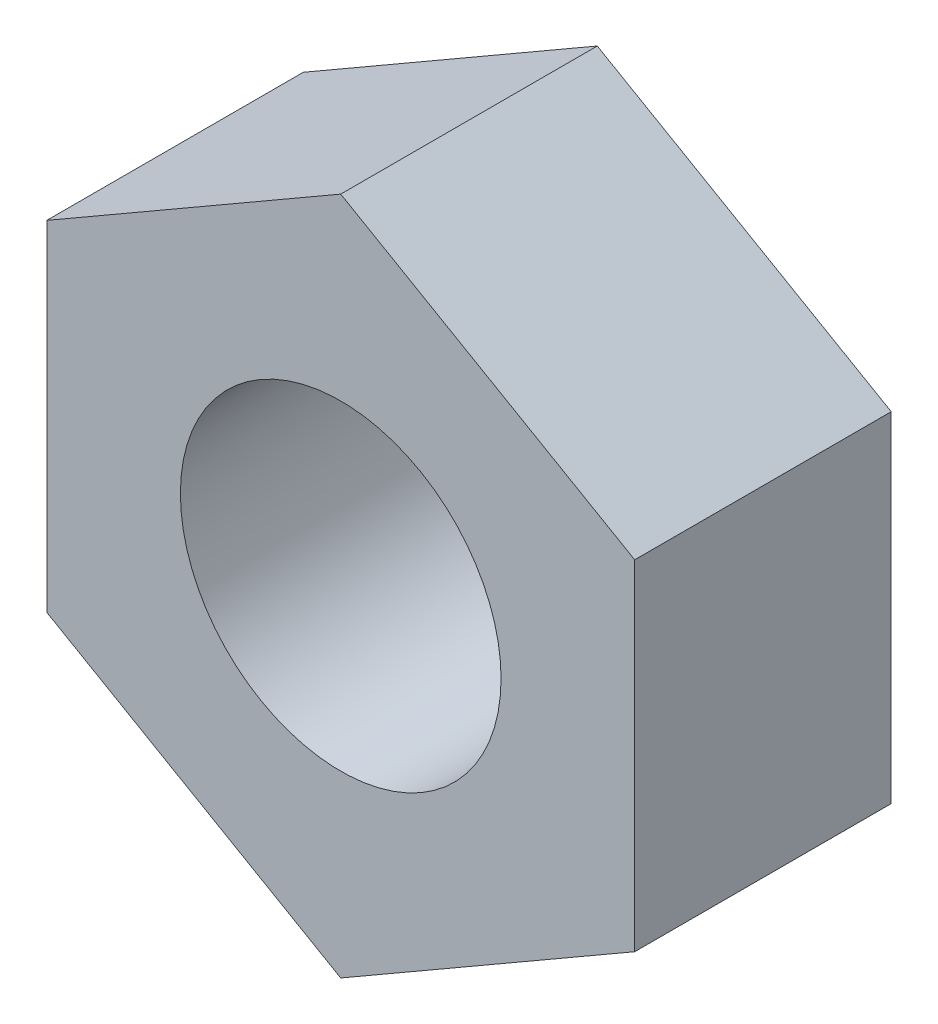
SolidWorks part; units mm, degrees
material "AISI 304"
ref_plane "Alzado" through (0, 0, 0) normal (0, 0, 1) x (1, 0, 0)
ref_plane "Planta" through (0, 0, 0) normal (0, 1, 0) x (1, 0, 0)
ref_plane "Vista lateral" through (0, 0, 0) normal (1, 0, 0) x (0, 0, -1)
sketch "Sk_Cuerpo" plane through (0, 0, 0) normal (0, 0, 1) x (1, 0, 0)
  line L1 (0, -3.1754) -> (2.75, -1.5877)
  line L2 (2.75, -1.5877) -> (2.75, 1.5877)
  line L3 (2.75, 1.5877) -> (0, 3.1754)
  line L4 (0, 3.1754) -> (-2.75, 1.5877)
  line L5 (-2.75, 1.5877) -> (-2.75, -1.5877)
  line L6 (-2.75, -1.5877) -> (0, -3.1754)
  circle A0 centre (0, 0) radius 2.75 construction
  dimension "D1" = 5.5
extrude "Cuerpo" add sketch "Sk_Cuerpo" along normal blind 2.4
sketch "Sk_Agujero" plane through (0, 0, 0) normal (0, 0, 1) x (1, 0, 0)
  circle A0 centre (0, 0) radius 1.5
  dimension "D1" = 3
extrude "Agujero" cut sketch "Sk_Agujero" along normal blind 2.4
